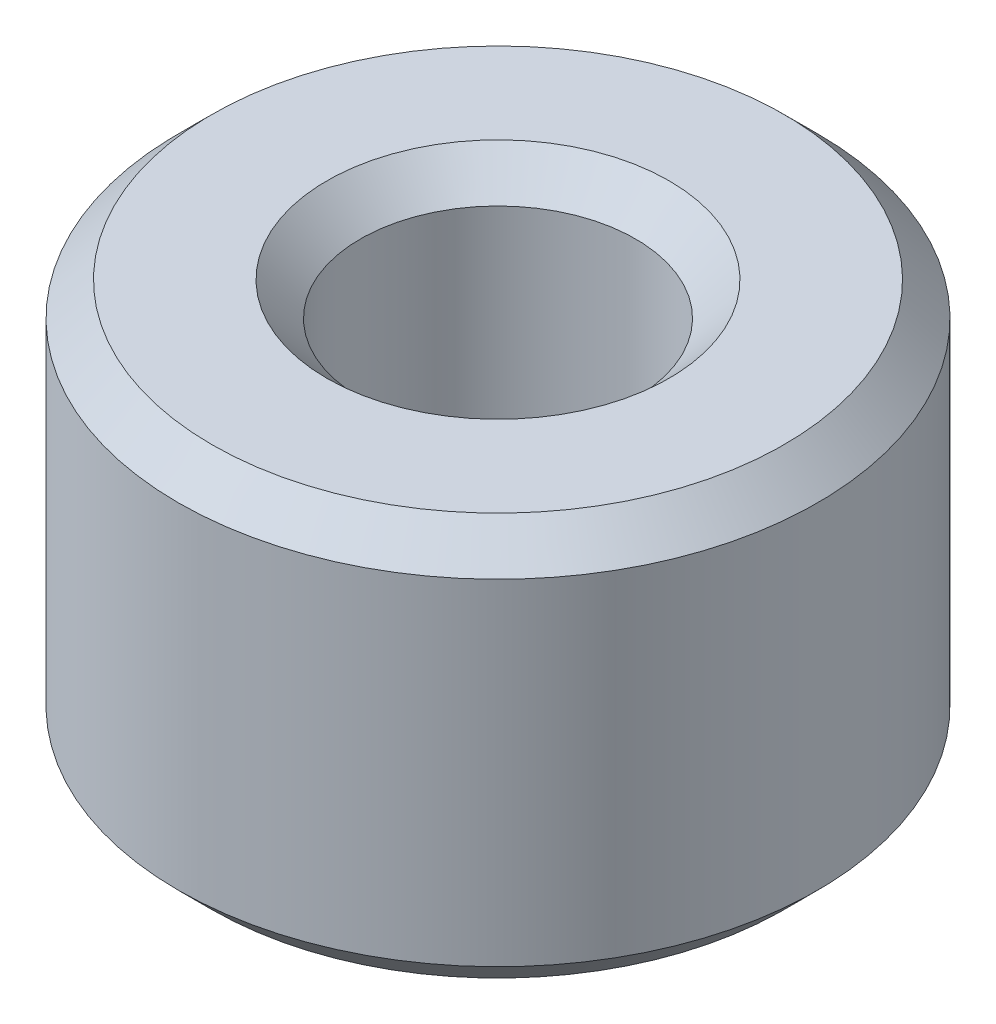
SolidWorks part; units mm, degrees
ref_plane "Front Plane" through (0, 0, 0) normal (0, 0, 1) x (1, 0, 0)
ref_plane "Top Plane" through (0, 0, 0) normal (0, 1, 0) x (1, 0, 0)
ref_plane "Right Plane" through (0, 0, 0) normal (1, 0, 0) x (0, 0, -1)
sketch "Sketch1" plane through (0, 0, 0) normal (0, 1, 0) x (1, 0, 0)
  circle A0 centre (0, 0) radius 2.05
  circle A1 centre (0, 0) radius 4.7625
  circle A2 centre (0, 0) radius 4.7625 construction
  dimension "D1" = 4.1
extrude "Boss-Extrude1" add sketch "Sketch1" along normal up to surface (6 mm away)
chamfer "Chamfer1" distance 0.5 angle 45 4 edges at (0, 0, 2.05) (0, 0, 4.7625) (0, 6, 2.05) (0, 6, 4.7625)
